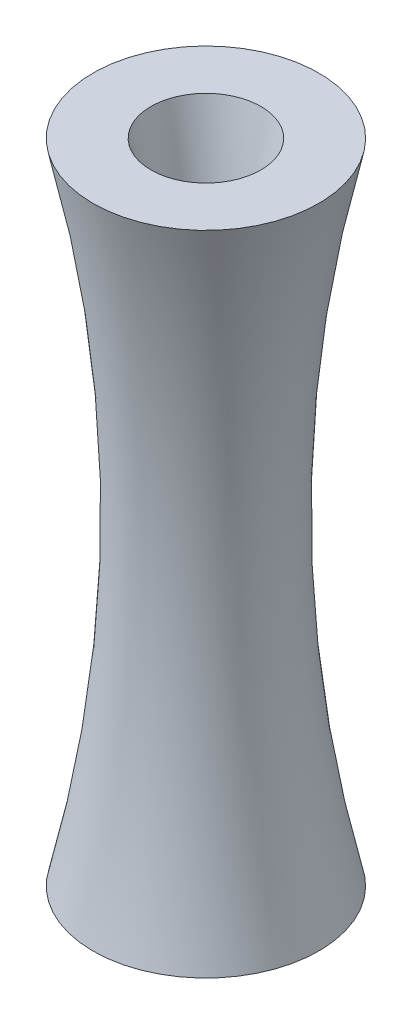
SolidWorks part; units mm, degrees
ref_plane "前视基准面" through (0, 0, 0) normal (0, 0, 1) x (1, 0, 0)
ref_plane "上视基准面" through (0, 0, 0) normal (0, 1, 0) x (1, 0, 0)
ref_plane "右视基准面" through (0, 0, 0) normal (1, 0, 0) x (0, 0, -1)
sketch "草图1" plane through (0, 0, 0) normal (0, 0, 1) x (1, 0, 0)
  line L0 (0, 0) -> (8.0146, 0)
  line L2 (8.0146, 45.9502) -> (0, 45.9502)
  line L3 (0, 45.9502) -> (0, 0)
  arc A0 (8.0146, 45.9502) -> (8.0146, 0) centre (103.1037, 22.9751) ccw
revolve "旋转1" add sketch "草图1" angle 360 about L3
shell "抽壳1" thickness 4
